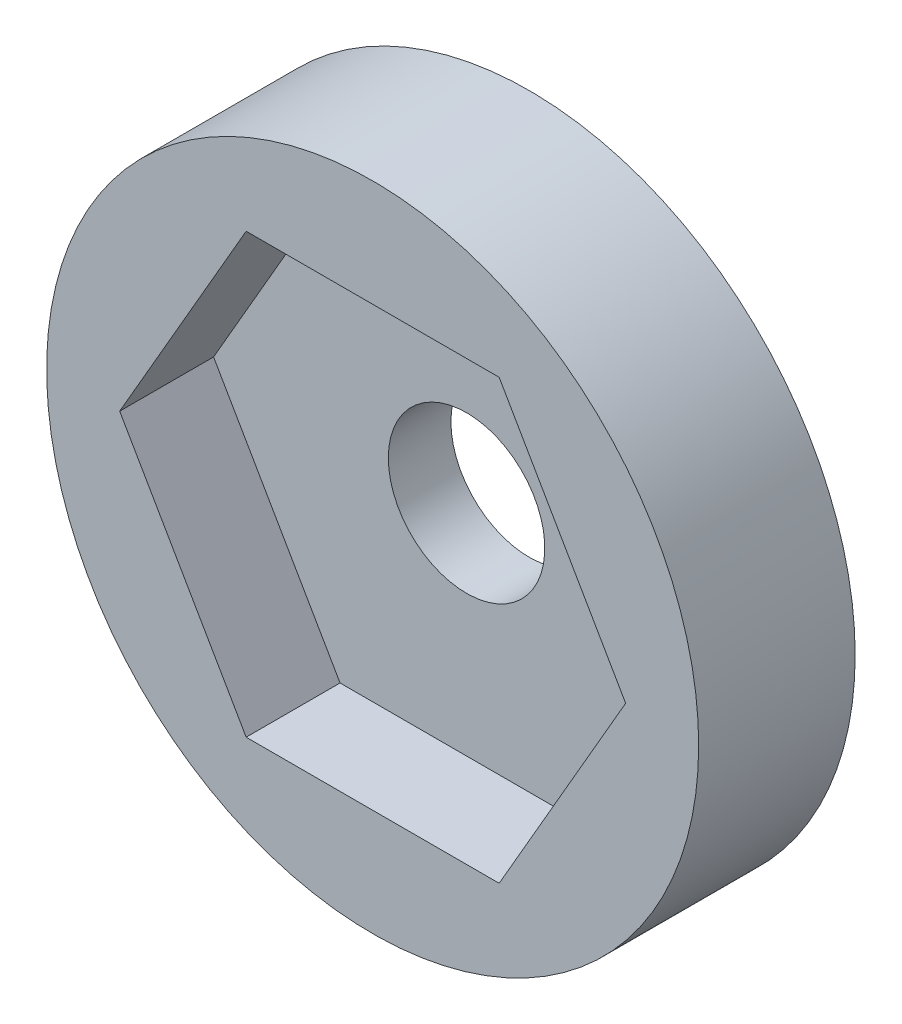
SolidWorks part; units mm, degrees
ref_plane "前视基准面" through (0, 0, 0) normal (0, 0, 1) x (1, 0, 0)
ref_plane "上视基准面" through (0, 0, 0) normal (0, 1, 0) x (1, 0, 0)
ref_plane "右视基准面" through (0, 0, 0) normal (1, 0, 0) x (0, 0, -1)
sketch "草图1" plane through (0, 0, 0) normal (0, 0, 1) x (1, 0, 0)
  circle A0 centre (0, 0) radius 12.5
  dimension "D1" = 25
extrude "凸台-拉伸1" add sketch "草图1" along normal blind 6
sketch "草图2" plane through (0, 0, 6) normal (0, 0, 1) x (1, 0, 0)
  line L1 (9.6995, 0) -> (4.8497, 8.4)
  line L2 (4.8497, 8.4) -> (-4.8497, 8.4)
  line L3 (-4.8497, 8.4) -> (-9.6995, 0)
  line L4 (-9.6995, 0) -> (-4.8497, -8.4)
  line L5 (-4.8497, -8.4) -> (4.8497, -8.4)
  line L6 (4.8497, -8.4) -> (9.6995, 0)
  circle A0 centre (0, 0) radius 8.4 construction
  dimension "D1" = 16.8
extrude "切除-拉伸1" cut sketch "草图2" against normal blind 3.6
sketch "草图3" plane through (0, 0, 0) normal (0, 0, -1) x (-1, 0, 0)
  circle A0 centre (0, 0) radius 3
  dimension "D1" = 6
extrude "切除-拉伸2" cut sketch "草图3" against normal blind 2.4
